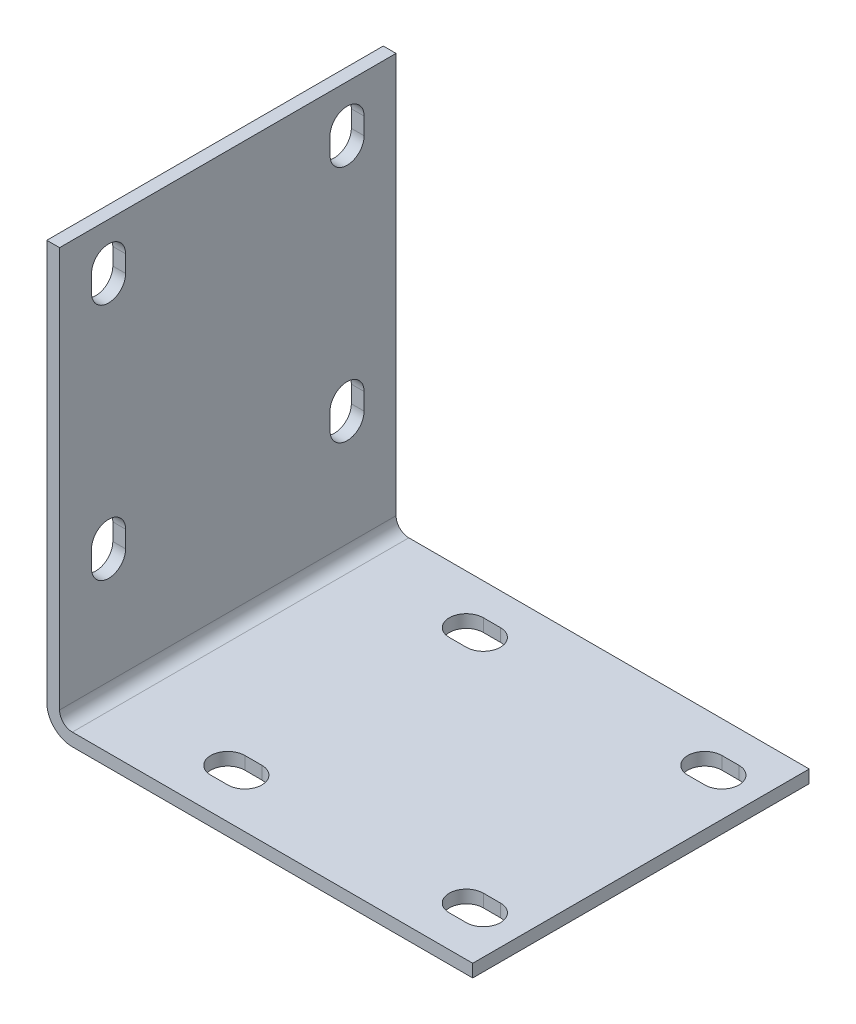
SolidWorks part; units mm, degrees
ref_plane "Front Plane" through (0, 0, 0) normal (0, 0, 1) x (1, 0, 0)
ref_plane "Top Plane" through (0, 0, 0) normal (0, 1, 0) x (1, 0, 0)
ref_plane "Right Plane" through (0, 0, 0) normal (1, 0, 0) x (0, 0, -1)
sketch "Sketch1" plane through (0, 0, 0) normal (0, 0, 1) x (1, 0, 0)
  line L0 (-9.525, 149.225) -> (-4.7625, 149.225)
  line L1 (-4.7625, 149.225) -> (-4.7625, 0)
  line L2 (0, -4.7625) -> (149.225, -4.7625)
  line L3 (149.225, -4.7625) -> (149.225, -9.525)
  line L4 (149.225, -9.525) -> (0, -9.525)
  line L5 (-9.525, 0) -> (-9.525, 149.225)
  arc A0 (-4.7625, 0) -> (0, -4.7625) centre (0, 0) ccw
  arc A1 (0, -9.525) -> (-9.525, 0) centre (0, 0) cw
  point P10 (0, 0)
  point P11 (0, 0)
  point P12 (0, 0)
  point P14 (-17.5519, 0)
  dimension "D4" = 4.7625
  dimension "D1" = 158.75
  dimension "D2" = 4.7625
  dimension "D3" = 158.75
extrude "Boss-Extrude1" add sketch "Sketch1" along normal mid plane 125.4125
ref_plane "Plane1" through (0, 0, 0) normal (0.7071, -0.7071, 0) x (-0.7071, -0.7071, 0)
sketch "Sketch2" plane through (-4.7625, 0, 0) normal (1, 0, 0) x (0, 0, -1)
  line L0 (-50.8, 134.9375) -> (-50.8, 128.5875)
  line L1 (-38.1, 128.5875) -> (-38.1, 134.9375)
  line L2 (-50.8, 46.0375) -> (-50.8, 39.6875)
  line L3 (-38.1, 39.6875) -> (-38.1, 46.0375)
  line L4 (38.1, 39.6875) -> (38.1, 46.0375)
  line L5 (50.8, 46.0375) -> (50.8, 39.6875)
  line L6 (38.1, 134.9375) -> (38.1, 128.5875)
  line L7 (50.8, 128.5875) -> (50.8, 134.9375)
  line L8 (-62.7063, 149.225) -> (62.7063, 149.225) construction
  line L9 (-44.45, 134.9375) -> (44.45, 134.9375) construction
  arc A0 (-50.8, 128.5875) -> (-38.1, 128.5875) centre (-44.45, 128.5875) ccw
  arc A1 (-38.1, 134.9375) -> (-50.8, 134.9375) centre (-44.45, 134.9375) ccw
  arc A2 (-50.8, 39.6875) -> (-38.1, 39.6875) centre (-44.45, 39.6875) ccw
  arc A3 (-38.1, 46.0375) -> (-50.8, 46.0375) centre (-44.45, 46.0375) ccw
  arc A4 (38.1, 46.0375) -> (50.8, 46.0375) centre (44.45, 46.0375) cw
  arc A5 (50.8, 39.6875) -> (38.1, 39.6875) centre (44.45, 39.6875) cw
  arc A6 (38.1, 128.5875) -> (50.8, 128.5875) centre (44.45, 128.5875) ccw
  arc A7 (50.8, 134.9375) -> (38.1, 134.9375) centre (44.45, 134.9375) ccw
  point P23 (0, 134.9375)
  point P29 (-44.45, 141.2875)
  point P30 (-44.45, 122.2375)
  point P34 (-44.45, 52.3875)
  dimension "D1" = 12.7
  dimension "D2" = 19.05
  dimension "D3" = 7.9375
  dimension "D4" = 69.85
  dimension "D5" = 76.2
extrude "Cut-Extrude1" cut sketch "Sketch2" against normal through all
mirror "Mirror1" about plane through (0, 0, 0) normal (0.7071, -0.7071, 0) of "Cut-Extrude1"
